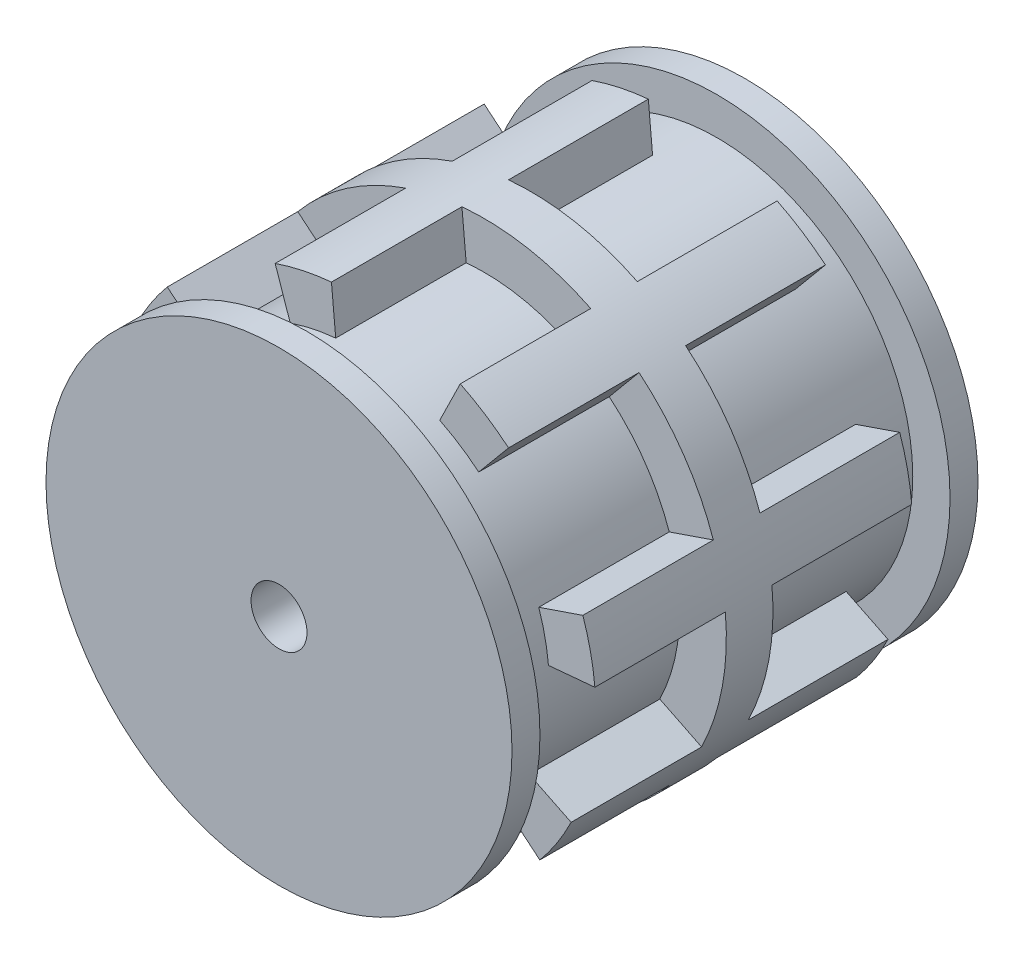
SolidWorks part; units mm, degrees
ref_plane "Alzado" through (0, 0, 0) normal (0, 0, 1) x (1, 0, 0)
ref_plane "Planta" through (0, 0, 0) normal (0, 1, 0) x (1, 0, 0)
ref_plane "Vista lateral" through (0, 0, 0) normal (1, 0, 0) x (0, 0, -1)
sketch "Croquis1" plane through (0, 0, 0) normal (0, 0, 1) x (1, 0, 0)
  circle A0 centre (0, 0) radius 12.5
  dimension "D1" = 25
extrude "Saliente-Extruir1" add sketch "Croquis1" along normal blind 25
sketch "Croquis2" plane through (0, 0, 0) normal (1, 0, 0) x (0, 0, -1)
  line L0 (0, 12.5) -> (-25, 12.5) construction
  line L1 (-23.5, 12.5) -> (-1.5, 12.5)
  line L2 (-23.5, 12.5) -> (-23.5, 10.5)
  line L3 (-23.5, 10.5) -> (-1.5, 10.5)
  line L4 (-1.5, 12.5) -> (-1.5, 10.5)
  line L5 (-25, 12.5) -> (-25, -12.5) construction
  line L6 (0, -12.5) -> (0, 12.5) construction
  line L7 (-31.8796, 0) -> (2.8885, 0) construction
  dimension "D1" = 1.5
  dimension "D2" = 2
  dimension "D3" = 1.5
revolve "Cortar-Revolución1" cut sketch "Croquis2" angle 360 about L7
sketch "Croquis3" plane through (0, 0, 25) normal (0, 0, 1) x (1, 0, 0)
  circle A0 centre (0, 0) radius 1.5
  dimension "D1" = 3
extrude "Cortar-Extruir1" cut sketch "Croquis3" against normal blind 25
ref_plane "Plano1" through (10.5, 0, 0) normal (1, 0, 0) x (0, 0, -1)
sketch "Croquis4" plane through (10.5, 0, 0) normal (1, 0, 0) x (0, 0, -1)
  line L0 (-23.5, -10.5) -> (-23.5, 10.5) construction
  line L1 (-21, 3.4594) -> (-4, 3.4594)
  line L2 (-21, 3.4594) -> (-21, 0.9594)
  line L3 (-21, 0.9594) -> (-4, 0.9594)
  line L4 (-4, 3.4594) -> (-4, 0.9594)
  line L6 (-1.5, 10.5) -> (-1.5, -10.5) construction
  dimension "D1" = 2.5
  dimension "D2" = 2.5
  dimension "D3" = 2.5
wrap "Envolver1" sketch "Croquis4" wrap type emboss source sketch "Croquis4" thickness 2.5 face at (10.5, 0, 1.5) parameters "D1"=2.5
pattern_circular "MatrizC1" count 8 over 360 about axis through (0, 0, 0) along (0, 0, 1) of "Envolver1"
sketch "Croquis5" plane through (0, 0, 0) normal (0, 1, 0) x (1, 0, 0)
  line L0 (10.5, -23.5) -> (10.5, -1.5) construction
  line L1 (10.5, -11.5) -> (13, -11.5)
  line L2 (10.5, -11.5) -> (10.5, -14)
  line L3 (10.5, -14) -> (13, -14)
  line L4 (13, -11.5) -> (13, -14)
  line L5 (-10.5, -1.5) -> (10.5, -1.5) construction
  line L6 (0, 6.4432) -> (0, -30.4411) construction
  dimension "D1" = 2.5
  dimension "D2" = 2.5
  dimension "D3" = 10
revolve "Revolución1" add sketch "Croquis5" angle 360 about L6
